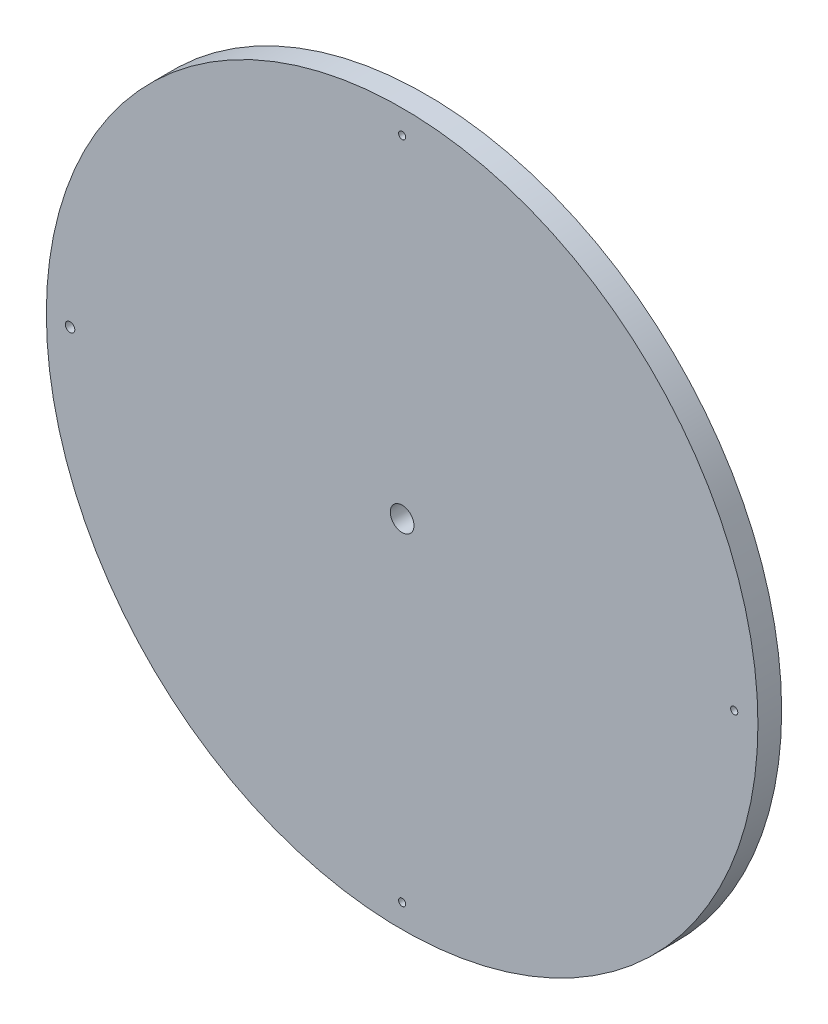
SolidWorks part; units mm, degrees
ref_plane "Front Plane" through (0, 0, 0) normal (0, 0, 1) x (1, 0, 0)
ref_plane "Top Plane" through (0, 0, 0) normal (0, 1, 0) x (1, 0, 0)
ref_plane "Right Plane" through (0, 0, 0) normal (1, 0, 0) x (0, 0, -1)
sketch "Sketch1" plane through (0, 0, 0) normal (0, 0, 1) x (1, 0, 0)
  circle A0 centre (0, 0) radius 150
  dimension "D1" = 300
extrude "Boss-Extrude1" add sketch "Sketch1" along normal blind 10 contours A0
sketch "Sketch2" plane through (0, 0, 10) normal (0, 0, 1) x (1, 0, 0)
  line L0 (-150, 0) -> (150, 0)
  line L1 (0, 150) -> (0, -150)
  circle A0 centre (0, 0) radius 150 construction
  point P8 (0, 140)
  point P9 (-140, 0)
  point P10 (0, -140)
  point P11 (140, 0)
  dimension "D1" = 10
  dimension "D2" = 10
  dimension "D3" = 10
  dimension "D4" = 10
sketch "Sketch3" plane through (0, 0, 10) normal (0, 0, 1) x (1, 0, 0)
  circle A0 centre (0, 140) radius 1.5
  circle A1 centre (140, 0) radius 1.5
  circle A2 centre (-140, 0) radius 1.5
  circle A3 centre (0, -140) radius 1.5
extrude "Cut-Extrude1" cut sketch "Sketch3" against normal blind 10 contours A0
sketch "Sketch5" plane through (0, 0, 10) normal (0, 0, 1) x (1, 0, 0)
  circle A0 centre (140, 0) radius 1.5
  circle A1 centre (0, -140) radius 1.5
  circle A2 centre (-140, 0) radius 2
extrude "Cut-Extrude2" cut sketch "Sketch5" against normal blind 10 contours A1 | A2 | A0
sketch "Sketch6" plane through (0, 0, 10) normal (0, 0, 1) x (1, 0, 0)
  circle A0 centre (0, 0) radius 5
extrude "Cut-Extrude8" cut sketch "Sketch6" against normal blind 10
